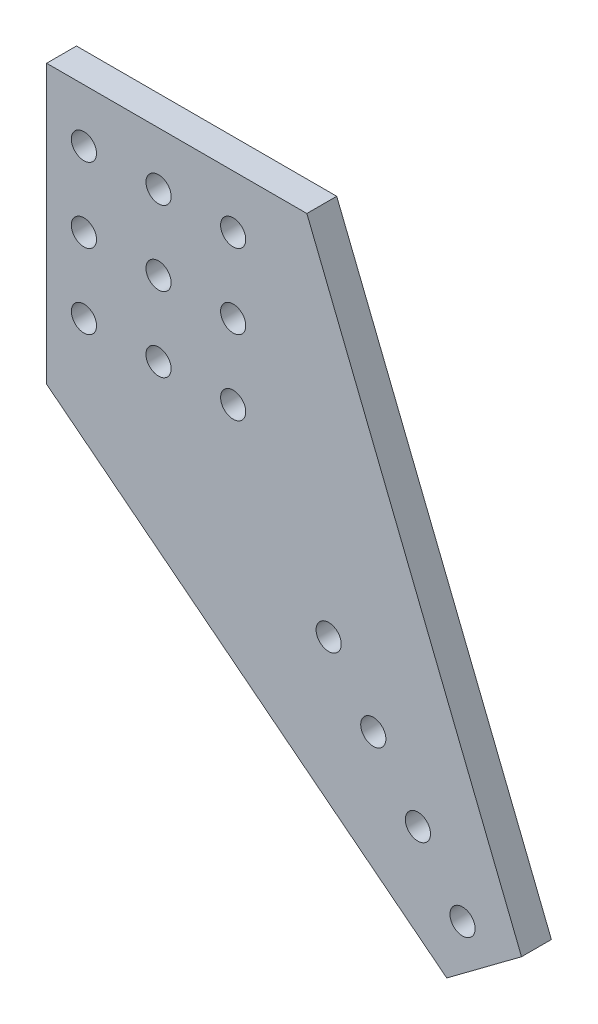
SolidWorks part; units mm, degrees
ref_plane "前视基准面" through (0, 0, 0) normal (0, 0, 1) x (1, 0, 0)
ref_plane "上视基准面" through (0, 0, 0) normal (0, 1, 0) x (1, 0, 0)
ref_plane "右视基准面" through (0, 0, 0) normal (1, 0, 0) x (0, 0, -1)
sketch "草图1" plane through (0, 0, 0) normal (0, 0, -1) x (1, 0, 0)
  line L0 (0, 0) -> (1492, 2000) construction
  line L1 (1492, 2000) -> (1492, 0) construction
  line L2 (1492, 0) -> (0, 0) construction
  line L3 (-120, 161) -> (-120, -137)
  line L4 (-120, -137) -> (159, -137)
  line L5 (159, -137) -> (389.1282, 438)
  line L6 (-120, 161) -> (308.9746, 497.7946)
  line L7 (308.9746, 497.7946) -> (389.1282, 438)
  circle A0 centre (0, 0) radius 13.5
  circle A1 centre (182.3736, 244.4686) radius 13.5
  circle A2 centre (230.2092, 308.5915) radius 13.5
  circle A3 centre (278.0449, 372.7144) radius 13.5
  circle A4 centre (325.8806, 436.8373) radius 13.5
  circle A5 centre (-80, 0) radius 13.5
  circle A6 centre (80, 0) radius 13.5
  circle A7 centre (-80, -80) radius 13.5
  circle A8 centre (0, -80) radius 13.5
  circle A9 centre (80, -80) radius 13.5
  circle A10 centre (-80, 80) radius 13.5
  circle A11 centre (0, 80) radius 13.5
  circle A12 centre (80, 80) radius 13.5
  dimension "D9" = 27
  dimension "D1" = 1492
  dimension "D2" = 2000
  dimension "D3" = 120
  dimension "D4" = 137
  dimension "D5" = 279
  dimension "D6" = 298
  dimension "D7" = 100
  dimension "D8" = 575
  dimension "D10" = 305
  dimension "D11" = 80
  dimension "D12" = 80
  dimension "D13" = 80
  dimension "D14" = 80
  dimension "D15" = 80
  dimension "D16" = 80
  dimension "D17" = 80
extrude "凸台-拉伸1" add sketch "草图1" along normal blind 32
